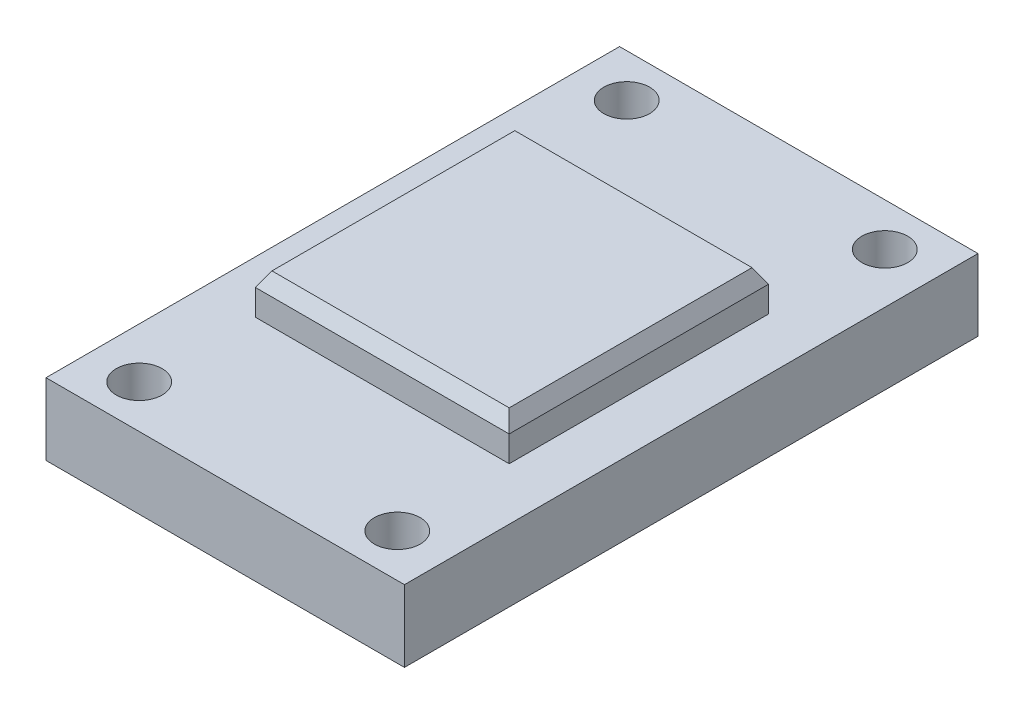
SolidWorks part; units mm, degrees
ref_plane "Спереди" through (0, 0, 0) normal (0, 0, 1) x (1, 0, 0)
ref_plane "Сверху" through (0, 0, 0) normal (0, 1, 0) x (1, 0, 0)
ref_plane "Справа" through (0, 0, 0) normal (1, 0, 0) x (0, 0, -1)
sketch "Sketch1" plane through (0, 0, 0) normal (0, 1, 0) x (1, 0, 0)
  line L1 (12.5, -20) -> (-12.5, -20)
  line L2 (12.5, -20) -> (12.5, 20)
  line L3 (12.5, 20) -> (-12.5, 20)
  line L4 (-12.5, -20) -> (-12.5, 20)
  line L5 (12.5, -20) -> (-12.5, 20) construction
  line L6 (12.5, 20) -> (-12.5, -20) construction
  point P0 (0, 0)
  dimension "D1" = 25
  dimension "D2" = 40
extrude "Boss-Extrude1" add sketch "Sketch1" along normal blind 5
sketch "Sketch4" plane through (0, 5, 0) normal (0, 1, 0) x (1, 0, 0)
  circle A0 centre (0, 0) radius 4.15
  dimension "D1" = 8.3
extrude "Cut-Extrude2" cut sketch "Sketch4" against normal through all
sketch "Sketch9" plane through (0, 5, 0) normal (0, 1, 0) x (1, 0, 0)
  line L1 (8.85, 9.0463) -> (-8.85, 9.0463)
  line L2 (8.85, 9.0463) -> (8.85, -9.0463)
  line L3 (8.85, -9.0463) -> (-8.85, -9.0463)
  line L4 (-8.85, 9.0463) -> (-8.85, -9.0463)
  line L5 (8.85, 9.0463) -> (-8.85, -9.0463) construction
  line L6 (8.85, -9.0463) -> (-8.85, 9.0463) construction
  line L7 (-3.7, -6.4086) -> (3.7, -6.4086) construction
  line L8 (3.7, -6.4086) -> (7.4, 0) construction
  line L9 (7.4, 0) -> (3.7, 6.4086) construction
  line L10 (3.7, 6.4086) -> (-3.7, 6.4086) construction
  line L11 (-3.7, 6.4086) -> (-7.4, 0) construction
  line L12 (-7.4, 0) -> (-3.7, -6.4086) construction
  circle A0 centre (0, 0) radius 7.4 construction
  point P0 (0, 0)
  dimension "D2" = 14.8
  dimension "D1" = 17.7
extrude "Boss-Extrude3" add sketch "Sketch9" along normal blind 2.8
sketch "Sketch6" plane through (0, 5, 0) normal (0, 1, 0) x (1, 0, 0)
  line L1 (-9, 17) -> (9, 17) construction
  line L2 (-9, 17) -> (-9, -17) construction
  line L3 (-9, -17) -> (9, -17) construction
  line L4 (9, 17) -> (9, -17) construction
  line L5 (-9, 17) -> (9, -17) construction
  line L6 (-9, -17) -> (9, 17) construction
  circle A0 centre (9, -17) radius 1.6
  circle A1 centre (-9, -17) radius 1.6
  circle A2 centre (-9, 17) radius 1.6
  circle A3 centre (9, 17) radius 1.6
  point P0 (0, 0)
  dimension "D1" = 3.2
  dimension "D2" = 18
  dimension "D3" = 34
extrude "Cut-Extrude4" cut sketch "Sketch6" against normal through all both and the other way through all
chamfer "Chamfer1" distance 1 angle 30 4 edges at (8.85, 7.8, 0) (0, 7.8, -9.0463) (-8.85, 7.8, 0) (0, 7.8, 9.0463)
sketch "Sketch10" plane through (0, 5, 0) normal (0, -1, 0) x (1, 0, 0)
  circle A0 centre (0, 0) radius 4.15
extrude "Boss-Extrude4" add sketch "Sketch10" along normal up to surface (5 mm away) up to face at (-9, 0, 18.6)
